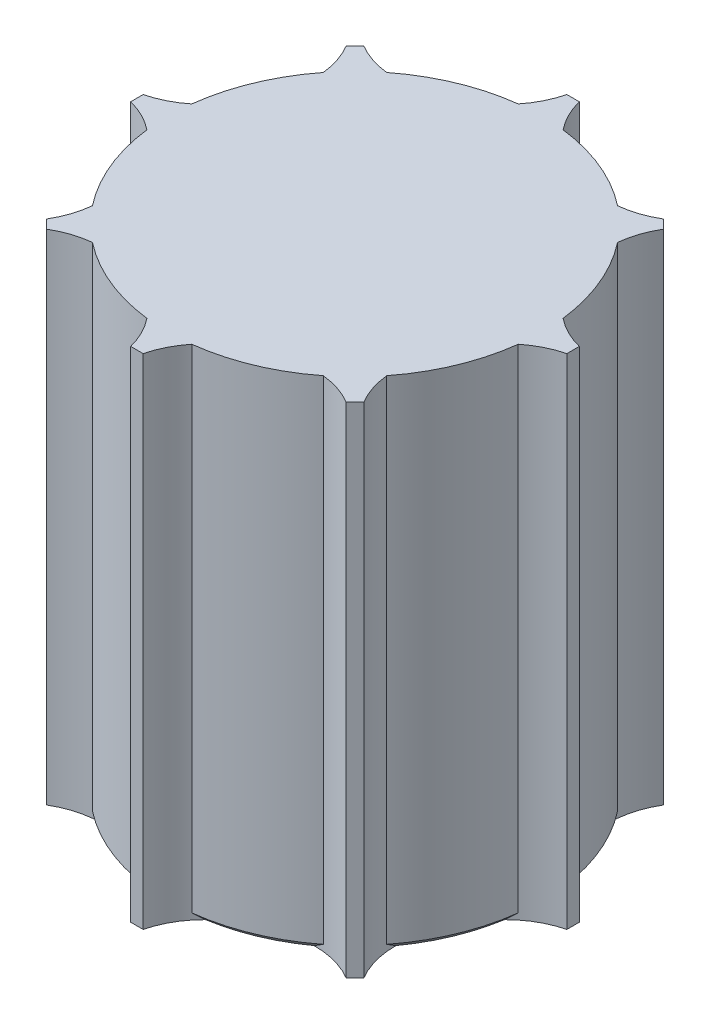
SolidWorks part; units mm, degrees
ref_plane "Front Plane" through (0, 0, 0) normal (0, 0, 1) x (1, 0, 0)
ref_plane "Top Plane" through (0, 0, 0) normal (0, 1, 0) x (1, 0, 0)
ref_plane "Right Plane" through (0, 0, 0) normal (1, 0, 0) x (0, 0, -1)
sketch "Sketch2" plane through (0, 0, 0) normal (0, 1, 0) x (1, 0, 0)
  circle A0 centre (0, 0) radius 6
  dimension "D1" = 12
extrude "Boss-Extrude2" add sketch "Sketch2" along normal blind 5
sketch "Sketch4" plane through (0, 5, 0) normal (0, 1, 0) x (1, 0, 0)
  circle A0 centre (0, 0) radius 15
  dimension "D1" = 30
extrude "Boss-Extrude3" add sketch "Sketch4" along normal blind 40
sketch "Sketch5" plane through (0, 45, 0) normal (0, 1, 0) x (1, 0, 0)
  line L0 (0, 0) -> (0, 20.8795) construction
  line L1 (-0.5, 17.4929) -> (0.5, 17.4929)
  line L2 (12.0158, 12.7229) -> (12.7229, 12.0158)
  line L3 (17.4929, 0.5) -> (17.4929, -0.5)
  line L4 (12.7229, -12.0158) -> (12.0158, -12.7229)
  line L5 (0.5, -17.4929) -> (-0.5, -17.4929)
  line L6 (-12.0158, -12.7229) -> (-12.7229, -12.0158)
  line L7 (-17.4929, -0.5) -> (-17.4929, 0.5)
  line L8 (-12.7229, 12.0158) -> (-12.0158, 12.7229)
  circle A0 centre (0, 0) radius 17.5
  circle A1 centre (0, 0) radius 15 construction
  circle A2 centre (0, 0) radius 15
  arc A3 (-1.8, 14.8916) -> (-0.5, 17.4929) centre (-7.0965, 19.164) ccw
  arc A4 (1.8, 14.8916) -> (0.5, 17.4929) centre (7.0965, 19.164) cw
  arc A5 (9.2572, 11.8027) -> (12.0158, 12.7229) centre (8.5331, 18.569) ccw
  arc A6 (11.8027, 9.2572) -> (12.7229, 12.0158) centre (18.569, 8.5331) cw
  arc A7 (14.8916, 1.8) -> (17.4929, 0.5) centre (19.164, 7.0965) ccw
  arc A8 (14.8916, -1.8) -> (17.4929, -0.5) centre (19.164, -7.0965) cw
  arc A9 (11.8027, -9.2572) -> (12.7229, -12.0158) centre (18.569, -8.5331) ccw
  arc A10 (9.2572, -11.8027) -> (12.0158, -12.7229) centre (8.5331, -18.569) cw
  arc A11 (1.8, -14.8916) -> (0.5, -17.4929) centre (7.0965, -19.164) ccw
  arc A12 (-1.8, -14.8916) -> (-0.5, -17.4929) centre (-7.0965, -19.164) cw
  arc A13 (-9.2572, -11.8027) -> (-12.0158, -12.7229) centre (-8.5331, -18.569) ccw
  arc A14 (-11.8027, -9.2572) -> (-12.7229, -12.0158) centre (-18.569, -8.5331) cw
  arc A15 (-14.8916, -1.8) -> (-17.4929, -0.5) centre (-19.164, -7.0965) ccw
  arc A16 (-14.8916, 1.8) -> (-17.4929, 0.5) centre (-19.164, 7.0965) cw
  arc A17 (-11.8027, 9.2572) -> (-12.7229, 12.0158) centre (-18.569, 8.5331) ccw
  arc A18 (-9.2572, 11.8027) -> (-12.0158, 12.7229) centre (-8.5331, 18.569) cw
  point P57 (0, 0)
  circle M4 centre (0, 0) radius 15
  dimension "D1" = 35
  dimension "D2" = 0.5
  dimension "D3" = 1.8
  dimension "D4" = 8
extrude "Boss-Extrude4" add sketch "Sketch5" against normal blind 40 contours A2 A18 L8 A17 | L0 L1 A3 M4 | L0 A2 A4 L1 | A2 A6 L2 A5 | A2 A16 L7 A15 | A2 A14 L6 A13 | A2 A12 L5 A11 | A2 A10 L4 A9 | A2 A8 L3 A7
sketch "Sketch6" plane through (0, 45, 0) normal (0, 1, 0) x (1, 0, 0)
  circle A0 centre (0, 0) radius 15
  dimension "D1" = 30
chamfer "Chamfer1" distance 0.5 angle 45 1 edges at (0, 0, 6)
chamfer "Chamfer2" distance 0.5 angle 45 8 edges at (13.8582, 5, 5.7403) (13.8582, 5, -5.7403) (5.7403, 5, -13.8582) (-5.7403, 5, -13.8582) (-13.8582, 5, -5.7403) (-13.8582, 5, 5.7403) (-5.7403, 5, 13.8582) (5.7403, 5, 13.8582)
